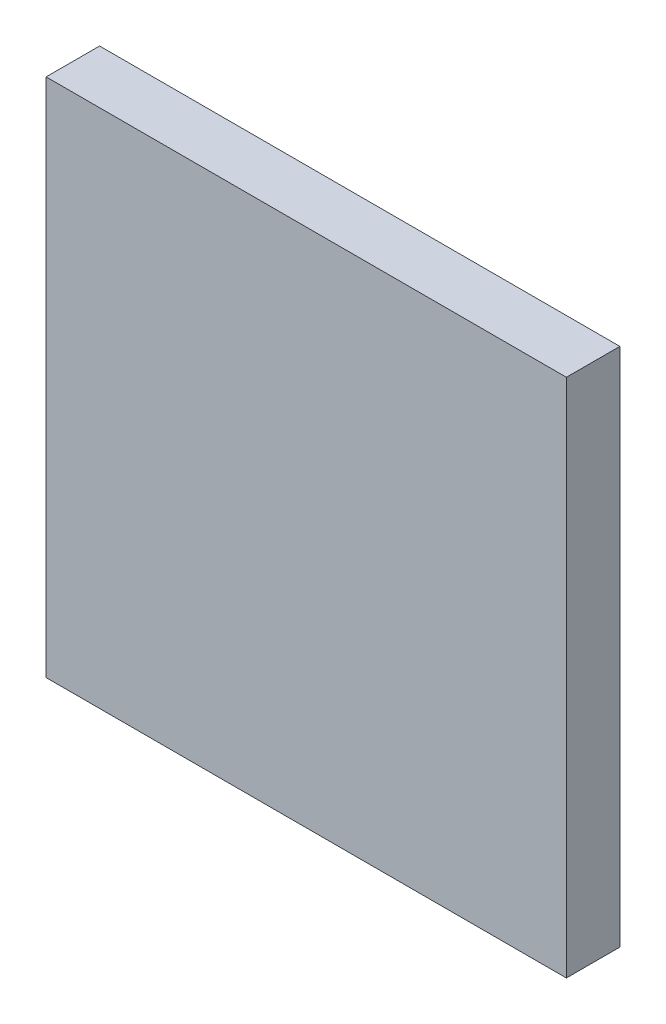
SolidWorks part; units mm, degrees
ref_plane "Front Plane" through (0, 0, 0) normal (0, 0, 1) x (1, 0, 0)
ref_plane "Top Plane" through (0, 0, 0) normal (0, 1, 0) x (1, 0, 0)
ref_plane "Right Plane" through (0, 0, 0) normal (1, 0, 0) x (0, 0, -1)
sketch "Sketch1" plane through (0, 0, 0) normal (0, 0, 1) x (1, 0, 0)
  line L0 (-4.8645, 4.8645) -> (4.8645, 4.8645)
  line L1 (4.8645, 4.8645) -> (4.8645, -4.8645)
  line L2 (4.8645, -4.8645) -> (-4.8645, -4.8645)
  line L3 (-4.8645, -4.8645) -> (-4.8645, 4.8645)
extrude "Component_Outline" add sketch "Sketch1" along normal blind 1 separate body
sketch3d "3DSketch1"
  line L0 (0, 0, 0) -> (1, 0, 0)
  line L1 (0, 0, 0) -> (0, 1, 0)
  line L2 (0, 0, 0) -> (0, 0, 1)
  point P0 (0, 0, 0)
